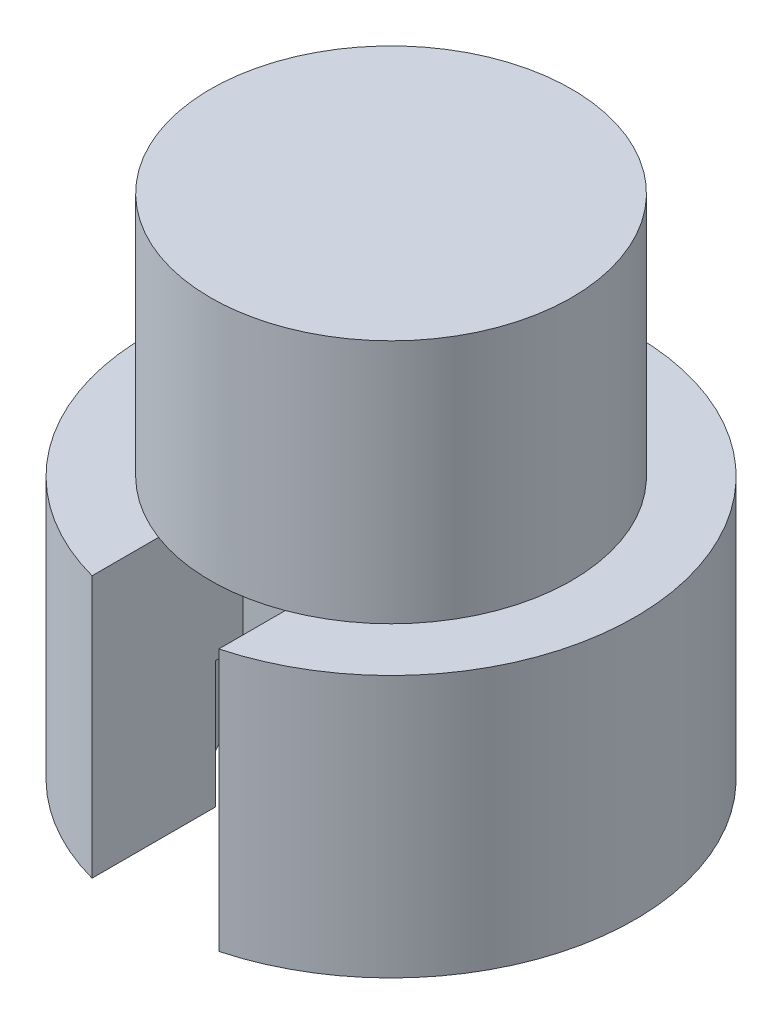
SolidWorks part; units mm, degrees
ref_plane "前视基准面" through (0, 0, 0) normal (0, 0, 1) x (1, 0, 0)
ref_plane "上视基准面" through (0, 0, 0) normal (0, 1, 0) x (1, 0, 0)
ref_plane "右视基准面" through (0, 0, 0) normal (1, 0, 0) x (0, 0, -1)
sketch "草图1" plane through (0, 0, 0) normal (0, 1, 0) x (1, 0, 0)
  circle A0 centre (0, 0) radius 4.275
  dimension "D1" = 8.55
extrude "凸台-拉伸1" add sketch "草图1" along normal blind 12
sketch "草图3" plane through (0, 0, 0) normal (0, -1, 0) x (1, 0, 0)
  circle A0 centre (0, 0) radius 4.275 construction
  circle A1 centre (0, 0) radius 4.275 construction
  circle A2 centre (0, 0) radius 5.775
  dimension "D1" = 1.5
extrude "凸台-拉伸2" add sketch "草图3" against normal blind 6.2
sketch "草图2" plane through (0, 0, 0) normal (0, -1, 0) x (1, 0, 0)
  circle A0 centre (0, 0) radius 3.05
  dimension "D1" = 6.1
extrude "切除-拉伸1" cut sketch "草图2" against normal blind 3
ref_plane "基准面1" through (0, 0, 6) normal (0, 0, 1) x (1, 0, 0)
sketch "草图4" plane through (0, 0, 6) normal (0, 0, 1) x (1, 0, 0)
  line L0 (5.775, 6.2) -> (-5.775, 6.2) construction
  line L1 (-1.5, 6.2) -> (1.5, 6.2)
  line L2 (-1.5, 6.2) -> (-1.5, 0)
  line L3 (-1.5, 0) -> (1.5, 0)
  line L4 (1.5, 6.2) -> (1.5, 0)
  line L5 (-5.775, 0) -> (5.775, 0) construction
  line L6 (0, 12) -> (0, 6.2) construction
  line L7 (4.275, 12) -> (-4.275, 12) construction
  dimension "D1" = 3
extrude "切除-拉伸2" cut sketch "草图4" against normal blind 4
